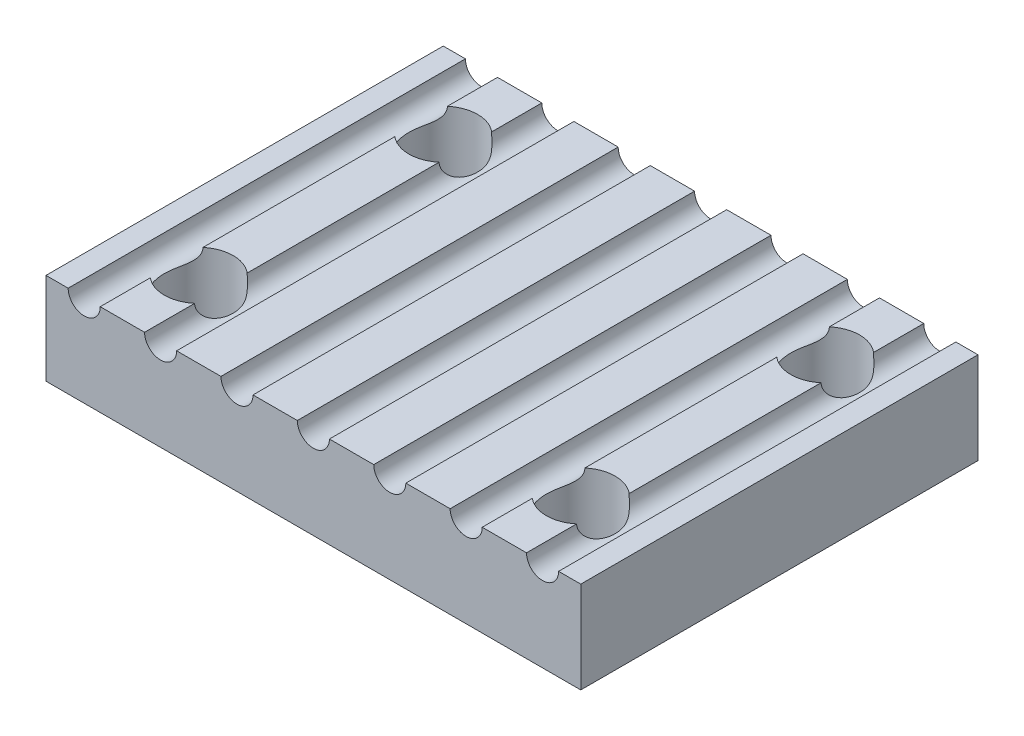
SolidWorks part; units mm, degrees
material "1060 合金"
ref_plane "前视基准面" through (0, 0, 0) normal (0, 0, 1) x (1, 0, 0)
ref_plane "上视基准面" through (0, 0, 0) normal (0, 1, 0) x (1, 0, 0)
ref_plane "右视基准面" through (0, 0, 0) normal (1, 0, 0) x (0, 0, -1)
sketch "草图1" plane through (0, 0, 0) normal (0, 1, 0) x (1, 0, 0)
  line L0 (0, -19.1161) -> (0, 19.1161) construction
  line L1 (-17.5, -13) -> (17.5, -13)
  line L2 (-17.5, -13) -> (-17.5, 13)
  line L3 (-17.5, 13) -> (17.5, 13)
  line L4 (17.5, -13) -> (17.5, 13)
  line L5 (-17.5, -13) -> (17.5, 13) construction
  line L6 (-17.5, 13) -> (17.5, -13) construction
  line L7 (-35.8226, 0) -> (35.8226, 0) construction
  circle A0 centre (-12.5, 8) radius 2.25
  circle A1 centre (12.5, 8) radius 2.25
  circle A2 centre (-12.5, -8) radius 2.25
  circle A3 centre (12.5, -8) radius 2.25
  point P0 (0, 0)
  point P6 (-12.5, 8)
  dimension "D5" = 4.5
  dimension "D1" = 35
  dimension "D2" = 26
  dimension "D3" = 12.5
  dimension "D4" = 8
extrude "凸台-拉伸1" add sketch "草图1" along normal blind 6
sketch "草图3" plane through (0, 0, 0) normal (0, 0, 1) x (1, 0, 0)
  line L0 (-17.5, 6) -> (17.5, 6) construction
  circle A0 centre (0, 6) radius 1.05
  circle A1 centre (5, 6) radius 1.05
  circle A2 centre (10, 6) radius 1.05
  circle A3 centre (15, 6) radius 1.05
  circle A4 centre (-5, 6) radius 1.05
  circle A5 centre (-10, 6) radius 1.05
  circle A6 centre (-15, 6) radius 1.05
  dimension "D1" = 2.1
  dimension "D2" = 4
  dimension "D3" = 4
extrude "切除-拉伸1" cut sketch "草图3" against normal through all both and the other way through all
